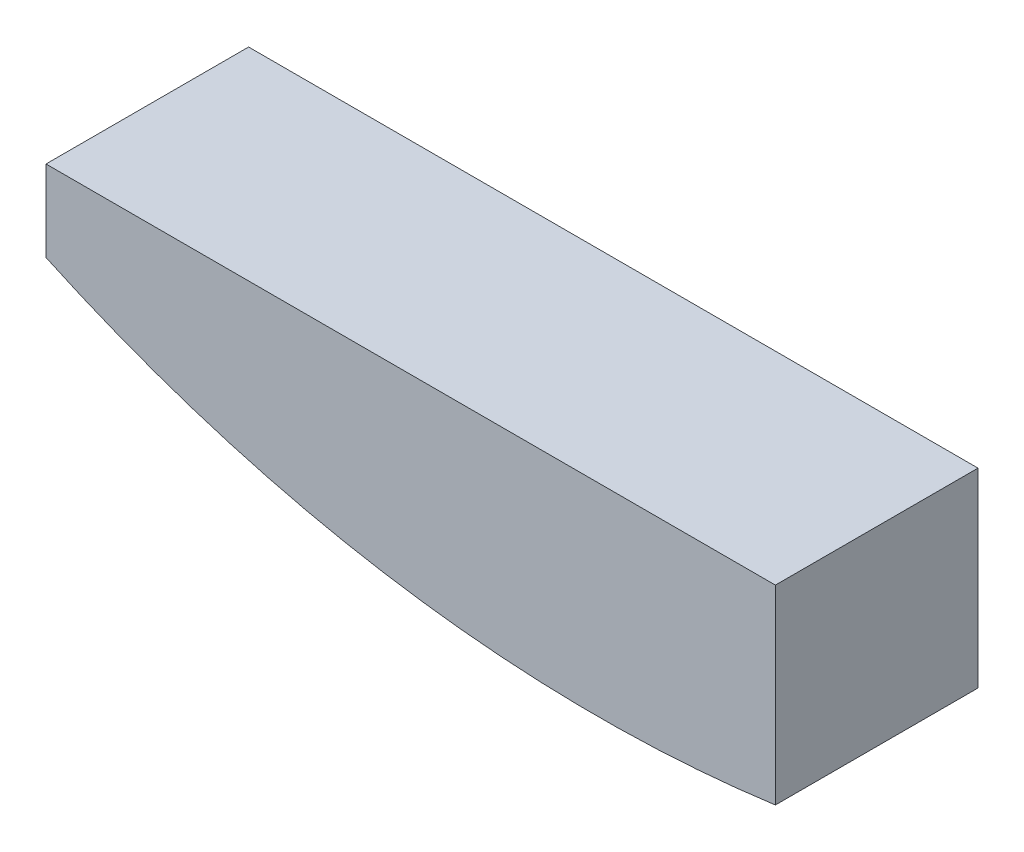
SolidWorks part; units mm, degrees
ref_plane "Front" through (0, 0, 0) normal (0, 0, 1) x (1, 0, 0)
ref_plane "Top" through (0, 0, 0) normal (0, 1, 0) x (1, 0, 0)
ref_plane "Right" through (0, 0, 0) normal (1, 0, 0) x (0, 0, -1)
sketch "Sketch2" plane through (0, 0, 0) normal (0, 1, 0) x (1, 0, 0)
  line L1 (0, 0) -> (18, 0)
  line L2 (0, 0) -> (0, 5)
  line L3 (0, 5) -> (18, 5)
  line L4 (18, 0) -> (18, 5)
  dimension "D1" = 18
  dimension "D2" = 5
extrude "Boss-Extrude1" add sketch "Sketch2" along normal blind 5
sketch "Sketch3" plane through (0, 0, 0) normal (0, 0, 1) x (1, 0, 0)
  line L1 (18, 5) -> (18, 2.3) construction
  line L2 (18, 5) -> (18, 0) construction
  line L4 (0, 5) -> (0, 0)
  line L5 (0, 2) -> (18, 2) construction
  line L7 (0, 0) -> (18, 0)
  line L8 (18, 0) -> (18, 2.3)
  line L9 (0, 5) -> (0, 0) construction
  arc A0 (0, 5) -> (18, 2.3) centre (13.6047, 34.3479) ccw
  point P1 (18, 2)
  point P14 (0, 2)
  dimension "D2" = 6
  dimension "D1" = 2.7
extrude "Cut-Extrude1" cut sketch "Sketch3" against normal through all
sketch "Sketch4" plane through (0, 5, 0) normal (0, 1, 0) x (1, 0, 0)
  line L4 (0, 5) -> (0, 0)
  line L5 (0, 0) -> (18, 0)
  line L6 (18, 0) -> (18, 5)
  line L7 (18, 5) -> (0, 5)
  line L8 (0, 5) -> (0, 0)
  line L9 (0, 0) -> (18, 0)
  line L10 (18, 0) -> (18, 5)
  line L11 (18, 5) -> (0, 5)
  dimension "D1" = 0
extrude "Boss-Extrude2" add sketch "Sketch4" along normal blind 2
